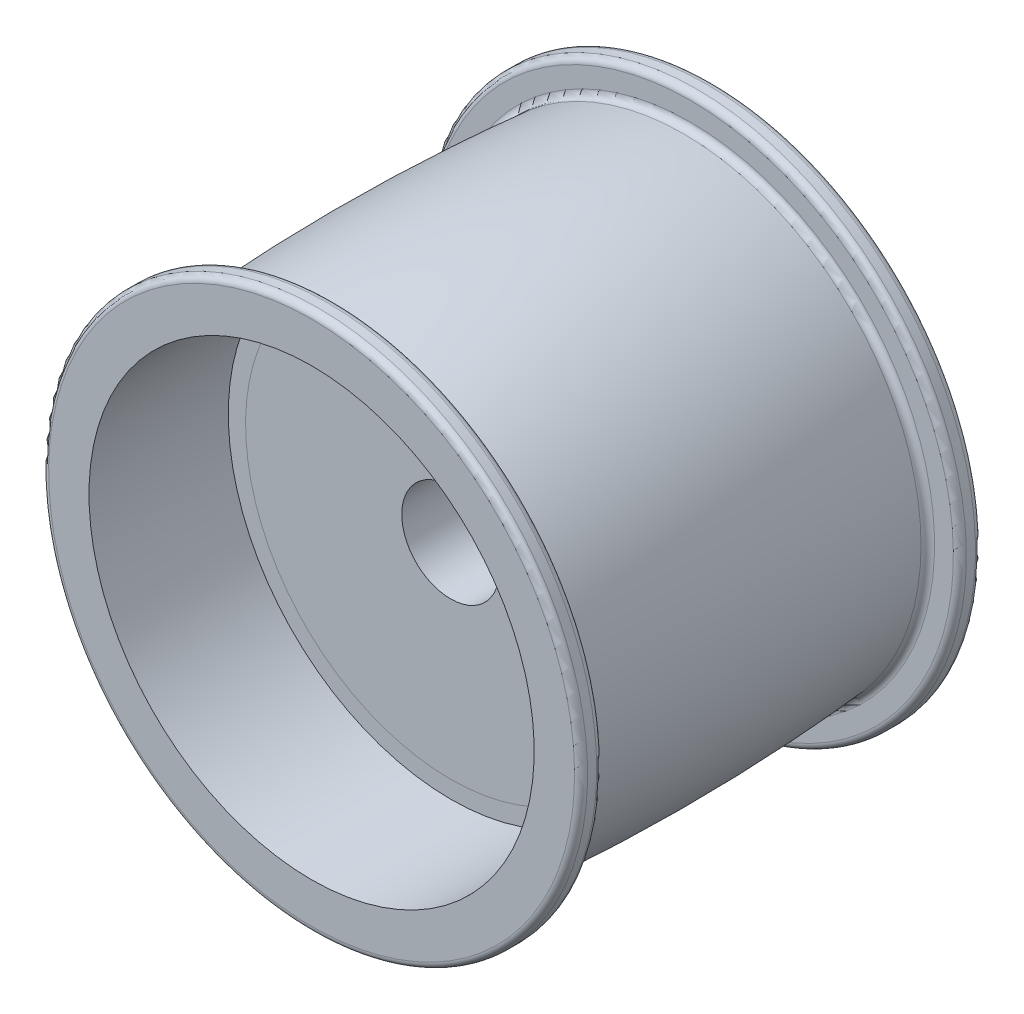
SolidWorks part; units mm, degrees
ref_plane "Front Plane" through (0, 0, 0) normal (0, 0, 1) x (1, 0, 0)
ref_plane "Top Plane" through (0, 0, 0) normal (0, 1, 0) x (1, 0, 0)
ref_plane "Right Plane" through (0, 0, 0) normal (1, 0, 0) x (0, 0, -1)
sketch "Sketch1" plane through (0, 0, 0) normal (1, 0, 0) x (0, 0, -1)
  line L0 (0, 0) -> (11.938, 0) construction
  line L1 (23.368, 26.289) -> (25.527, 26.289)
  line L2 (0, 20) -> (11.938, 20)
  line L4 (-13.589, 26.289) -> (-11.43, 26.289)
  line L5 (11.938, 20) -> (11.938, 21.717)
  line L6 (-13.589, 21.717) -> (0, 21.717)
  line L7 (-11.43, 26.289) -> (-11.43, 23.1297)
  line L9 (23.368, 26.289) -> (23.368, 23.1297)
  line L10 (11.938, 21.717) -> (25.527, 21.717)
  line L12 (-0.031, 20) -> (11.969, 20) construction
  line L13 (0, 20) -> (0, 21.717)
  line L16 (11.969, 4.7625) -> (-0.031, 4.7625) construction
  line L20 (-13.589, 21.717) -> (-13.589, 26.289)
  line L21 (25.527, 21.717) -> (25.527, 26.289)
  line L22 (-8.3185, 23.876) -> (20.2565, 23.876) construction
  line L24 (-0.031, 4.7625) -> (-0.031, 20) construction
  line L25 (11.969, 20) -> (11.969, 4.7625) construction
  line L26 (0, 21.717) -> (11.938, 21.717) construction
  line L27 (5.969, 21.717) -> (5.969, 23.876) construction
  line L28 (5.969, 23.876) -> (5.969, 0) construction
  line L29 (-0.031, 20) -> (-0.031, 20.031) construction
  line L30 (-11.43, 26.289) -> (23.368, 26.289) construction
  arc A0 (23.368, 23.1297) -> (-11.43, 23.1297) centre (5.969, -179.324) ccw
  point P10 (5.969, 20)
  point P12 (5.969, 20)
  point P31 (5.969, 26.289)
  point P33 (5.969, 0)
  point P34 (5.969, 23.876)
  point P36 (5.969, -23.876)
  dimension "D1" = 203.2
  dimension "A" = 52.578
  dimension "B" = 47.752
  dimension "C" = 34.798
  dimension "D" = 39.116
  dimension "D2" = 40
  dimension "D5" = 12
  dimension "Bore" = 9.525
  dimension "E" = 11.938
  dimension "Belt Size" = 28.575
revolve "Revolve1" add sketch "Sketch1" angle 360 about L0
fillet "Fillet1" radius 0.635 6 edges at (0, -26.289, -25.527) (0, -26.289, -23.368) (0, -26.289, 11.43) (0, -26.289, 13.589) (0, -23.1297, -23.368) (0, -23.1297, 11.43)
sketch "Sketch2" plane through (0, 0, 0) normal (1, 0, 0) x (0, 0, -1)
  line L0 (0, 0) -> (11.938, 0) construction
  line L2 (-0.031, 20) -> (11.969, 20)
  line L3 (-0.031, 20) -> (-0.031, 4.7625)
  line L4 (-0.031, 4.7625) -> (11.969, 4.7625)
  line L5 (11.969, 20) -> (11.969, 4.7625)
revolve "Revolve2" add sketch "Sketch2" angle 360 about L0
